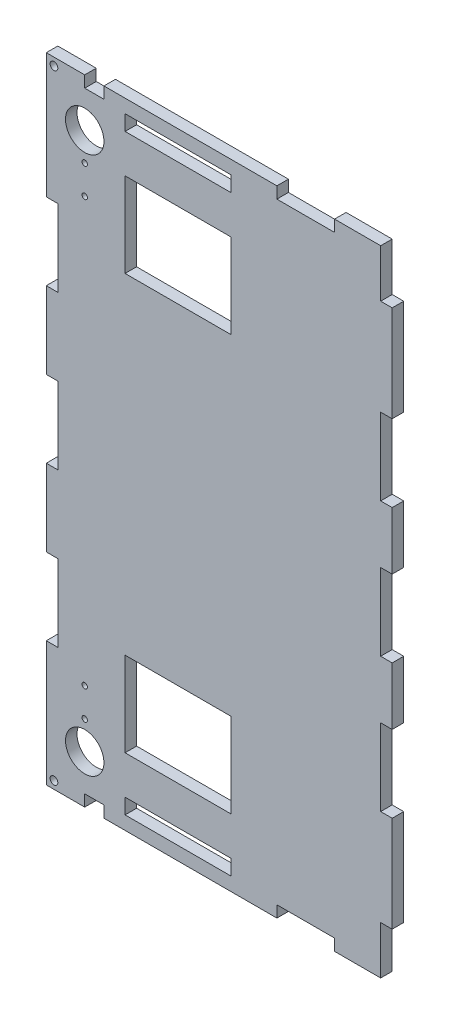
SolidWorks part; units mm, degrees
ref_plane "Plan de face" through (0, 0, 0) normal (0, 0, 1) x (1, 0, 0)
ref_plane "Plan de dessus" through (0, 0, 0) normal (0, 1, 0) x (1, 0, 0)
ref_plane "Plan de droite" through (0, 0, 0) normal (1, 0, 0) x (0, 0, -1)
sketch "Esquisse1" plane through (0, 0, 0) normal (0, 0, 1) x (1, 0, 0)
  line L1 (0, 0) -> (-180, 0)
  line L2 (0, 0) -> (0, 330)
  line L3 (0, 330) -> (-180, 330)
  line L4 (-180, 0) -> (-180, 330)
  dimension "D1" = 330
  dimension "D2" = 180
extrude "Boss.-Extru.1" add sketch "Esquisse1" along normal blind 6
sketch "Esquisse2" plane through (0, 0, 6) normal (0, 0, 1) x (1, 0, 0)
  line L0 (-9.0218, 165) -> (-189.0218, 165) construction
  line L1 (-139, 323) -> (-84, 323)
  line L2 (-139, 323) -> (-139, 315)
  line L3 (-139, 315) -> (-84, 315)
  line L4 (-84, 323) -> (-84, 315)
  line L5 (-139, 295) -> (-84, 295)
  line L6 (-139, 295) -> (-139, 251)
  line L7 (-139, 251) -> (-84, 251)
  line L8 (-84, 295) -> (-84, 251)
  line L9 (0, 330) -> (-180, 330) construction
  line L10 (-180, 330) -> (-180, 0) construction
  line L11 (-84, 7) -> (-84, 15)
  line L12 (-139, 7) -> (-139, 15)
  line L13 (-139, 7) -> (-84, 7)
  line L14 (-139, 15) -> (-84, 15)
  line L15 (-84, 35) -> (-84, 79)
  line L16 (-139, 79) -> (-84, 79)
  line L17 (-139, 35) -> (-84, 35)
  line L18 (-139, 35) -> (-139, 79)
  circle A0 centre (-176, 326) radius 2
  circle A1 centre (-160, 305) radius 10
  circle A2 centre (-160, 290.27) radius 1.4
  circle A3 centre (-160, 275.27) radius 1.4
  circle A4 centre (-160, 54.73) radius 1.4
  circle A5 centre (-160, 39.73) radius 1.4
  circle A6 centre (-160, 25) radius 10
  circle A7 centre (-176, 4) radius 2
  point P9 (-90, 330)
  dimension "D10" = 4
  dimension "D13" = 20
  dimension "D16" = 14.73
  dimension "D18" = 15
  dimension "D17" = 20
  dimension "D19" = 2.8
  dimension "D21" = 2.8
  dimension "D1" = 55
  dimension "D2" = 8
  dimension "D3" = 55
  dimension "D4" = 44
  dimension "D5" = 20
  dimension "D6" = 7
  dimension "D7" = 86
  dimension "D8" = 41
  dimension "D9" = 41
  dimension "D11" = 4
  dimension "D12" = 4
  dimension "D14" = 25
  dimension "D15" = 20
  dimension "D20" = 20
extrude "Enlèv. mat bloc moteur + bille" cut sketch "Esquisse2" against normal through all
sketch "Esquisse3" plane through (0, 0, 6) normal (0, 0, 1) x (1, 0, 0)
  line L0 (0, 0) -> (0, 330) construction
  line L1 (0, 330) -> (-180, 330) construction
  line L2 (0, 330) -> (-6, 330)
  line L3 (-180, 0) -> (0, 0) construction
  line L4 (-160, 0) -> (-150, 0)
  line L5 (-160, 0) -> (-160, 6)
  line L6 (-160, 6) -> (-150, 6)
  line L7 (-150, 0) -> (-150, 6)
  line L8 (-180, 330) -> (-180, 0) construction
  line L9 (0, 0) -> (0, 330) construction
  line L10 (-60, 0) -> (-30, 0)
  line L11 (-60, 0) -> (-60, 6)
  line L12 (-60, 6) -> (-30, 6)
  line L13 (-30, 0) -> (-30, 6)
  line L14 (-180, 145) -> (-174, 145)
  line L15 (-180, 65) -> (-174, 65)
  line L16 (-180, 65) -> (-180, 105)
  line L17 (-180, 105) -> (-174, 105)
  line L18 (-174, 65) -> (-174, 105)
  line L19 (-180, 145) -> (-180, 185)
  line L20 (-180, 185) -> (-174, 185)
  line L21 (-160, 330) -> (-150, 330)
  line L22 (-160, 330) -> (-160, 324)
  line L23 (-160, 324) -> (-150, 324)
  line L24 (-150, 330) -> (-150, 324)
  line L25 (0, 330) -> (0, 305)
  line L26 (-60, 330) -> (-30, 330)
  line L27 (-60, 330) -> (-60, 324)
  line L28 (-174, 145) -> (-174, 185)
  line L29 (-180, 225) -> (-174, 225)
  line L30 (-180, 225) -> (-180, 265)
  line L31 (-180, 265) -> (-174, 265)
  line L32 (-174, 225) -> (-174, 265)
  line L33 (-60, 324) -> (-30, 324)
  line L34 (-30, 330) -> (-30, 324)
  line L35 (0, 305) -> (-6, 305)
  line L36 (-6, 330) -> (-6, 305)
  line L37 (0, 255) -> (-6, 255)
  line L38 (0, 255) -> (0, 215)
  line L39 (0, 215) -> (-6, 215)
  line L40 (-6, 255) -> (-6, 215)
  line L42 (0, 185) -> (-6, 185)
  line L43 (0, 185) -> (0, 145)
  line L44 (0, 145) -> (-6, 145)
  line L45 (-6, 185) -> (-6, 145)
  line L46 (0, 115) -> (-6, 115)
  line L47 (0, 115) -> (0, 75)
  line L48 (0, 75) -> (-6, 75)
  line L49 (-6, 115) -> (-6, 75)
  line L50 (0, 0) -> (-6, 0)
  line L51 (0, 0) -> (0, 25)
  line L52 (0, 25) -> (-6, 25)
  line L53 (-6, 0) -> (-6, 25)
  dimension "D1" = 6
  dimension "D2" = 10
  dimension "D3" = 20
  dimension "D4" = 6
  dimension "D5" = 30
  dimension "D6" = 30
  dimension "D7" = 40
  dimension "D8" = 6
  dimension "D9" = 40
  dimension "D10" = 6
  dimension "D11" = 40
  dimension "D12" = 40
  dimension "D13" = 40
  dimension "D14" = 6
  dimension "D15" = 6
  dimension "D16" = 65
  dimension "D17" = 20
  dimension "D18" = 10
  dimension "D19" = 6
  dimension "D20" = 30
  dimension "D21" = 30
  dimension "D22" = 25
  dimension "D23" = 50
  dimension "D24" = 40
  dimension "D25" = 30
  dimension "D26" = 40
  dimension "D27" = 30
  dimension "D28" = 40
  dimension "D29" = 25
  dimension "D30" = 6
  dimension "D31" = 6
  dimension "D32" = 6
  dimension "D33" = 6
  dimension "D34" = 6
extrude "Enlèv. mat encoche" cut sketch "Esquisse3" against normal through all
